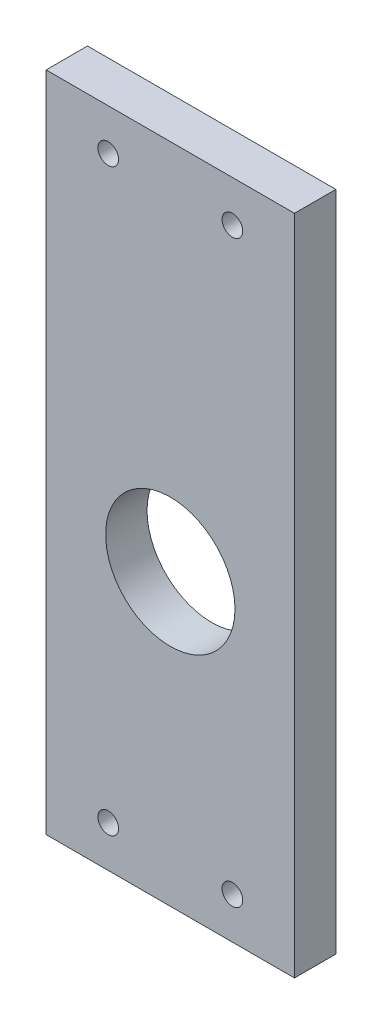
SolidWorks part; units mm, degrees
ref_plane "Front Plane" through (0, 0, 0) normal (0, 0, 1) x (1, 0, 0)
ref_plane "Top Plane" through (0, 0, 0) normal (0, 1, 0) x (1, 0, 0)
ref_plane "Right Plane" through (0, 0, 0) normal (1, 0, 0) x (0, 0, -1)
sketch "Sketch1" plane through (0, 0, 0) normal (0, 0, 1) x (1, 0, 0)
  line L1 (0, 0) -> (76.2, 0)
  line L2 (0, 0) -> (0, 203.2)
  line L3 (0, 203.2) -> (76.2, 203.2)
  line L4 (76.2, 0) -> (76.2, 203.2)
  dimension "D1" = 203.2
  dimension "D2" = 76.2
extrude "Boss-Extrude1" add sketch "Sketch1" along normal blind 12.7
sketch "Sketch2" plane through (0, 0, 12.7) normal (0, 0, 1) x (1, 0, 0)
  line L2 (0, 0) -> (76.2, 0) construction
  line L3 (76.2, 0) -> (76.2, 203.2) construction
  circle A0 centre (38.1, 88.9) radius 19.8438
  dimension "D1" = 39.6875
  dimension "D2" = 88.9
  dimension "D3" = 38.1
extrude "Cut-Extrude1" cut sketch "Sketch2" against normal up to surface (12.7 mm away) up to face at (38.1, 101.6, 0)
sketch "Sketch3" plane through (0, 0, 12.7) normal (0, 0, 1) x (1, 0, 0)
  line L0 (76.2, 203.2) -> (0, 203.2) construction
  line L1 (0, 0) -> (76.2, 0) construction
  line L2 (0, 203.2) -> (0, 0) construction
  line L3 (76.2, 0) -> (76.2, 203.2) construction
  circle A0 centre (19.05, 190.5) radius 3.175
  circle A1 centre (57.15, 190.5) radius 3.175
  circle A2 centre (19.05, 12.7) radius 3.175
  circle A3 centre (57.15, 12.7) radius 3.175
  dimension "D1" = 6.35
  dimension "D2" = 12.7
  dimension "D3" = 12.7
  dimension "D4" = 19.05
  dimension "D5" = 19.05
extrude "Cut-Extrude2" cut sketch "Sketch3" against normal up to surface (12.7 mm away) up to face at (18.2563, 88.9, 0)
